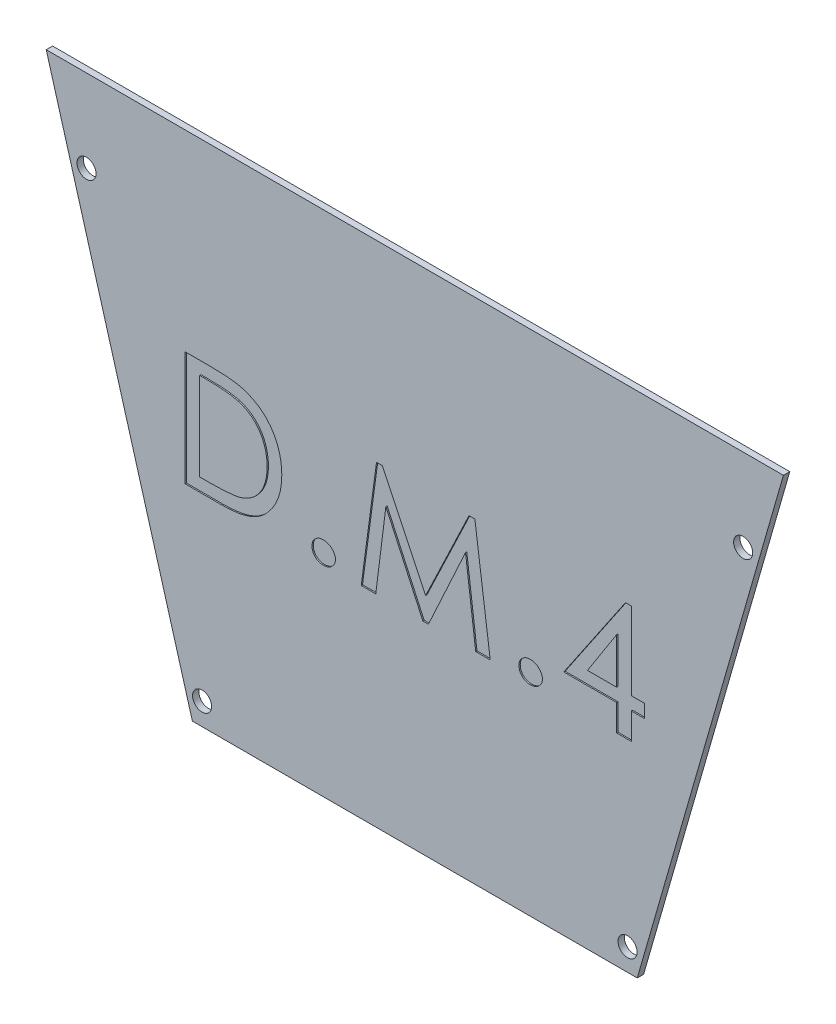
SolidWorks part; units mm, degrees
ref_plane "Front Plane" through (0, 0, 0) normal (0, 0, 1) x (1, 0, 0)
ref_plane "Top Plane" through (0, 0, 0) normal (0, 1, 0) x (1, 0, 0)
ref_plane "Right Plane" through (0, 0, 0) normal (1, 0, 0) x (0, 0, -1)
sketch "Sketch4" plane through (0, 0, 0) normal (0, 0, 1) x (1, 0, 0)
  line L0 (-47.4949, -80) -> (22.5051, -80)
  line L1 (22.5051, -80) -> (45.5051, 0)
  line L2 (45.5051, 0) -> (-70.4949, 0)
  line L3 (-70.4949, 0) -> (-47.4949, -80)
  circle A0 centre (-64.1562, -13) radius 1.5
  circle A1 centre (39.1663, -13) radius 1.5
  circle A2 centre (20.975, -76.5) radius 1.5
  circle A3 centre (-45.9649, -76.5) radius 1.5
extrude "Boss-Extrude2" add sketch "Sketch4" along normal blind 2
sketch "Sketch3" plane through (0, 0, 2) normal (0, 0, 1) x (1, 0, 0)
  text T0 "<b>D.M.4</b>" font "Century Gothic" height in points 68
extrude "Cut-Extrude3" cut sketch "Sketch3" against normal blind 1.2
sketch "Sketch5" plane through (0, 0, 2) normal (0, 0, 1) x (1, 0, 0)
  line L1 (-77.1201, 4.6174) -> (51.3299, 4.6174)
  line L2 (-77.1201, 4.6174) -> (-77.1201, -83.9504)
  line L3 (-77.1201, -83.9504) -> (51.3299, -83.9504)
  line L4 (51.3299, 4.6174) -> (51.3299, -83.9504)
extrude "Cut-Extrude4" cut sketch "Sketch5" against normal blind 1
